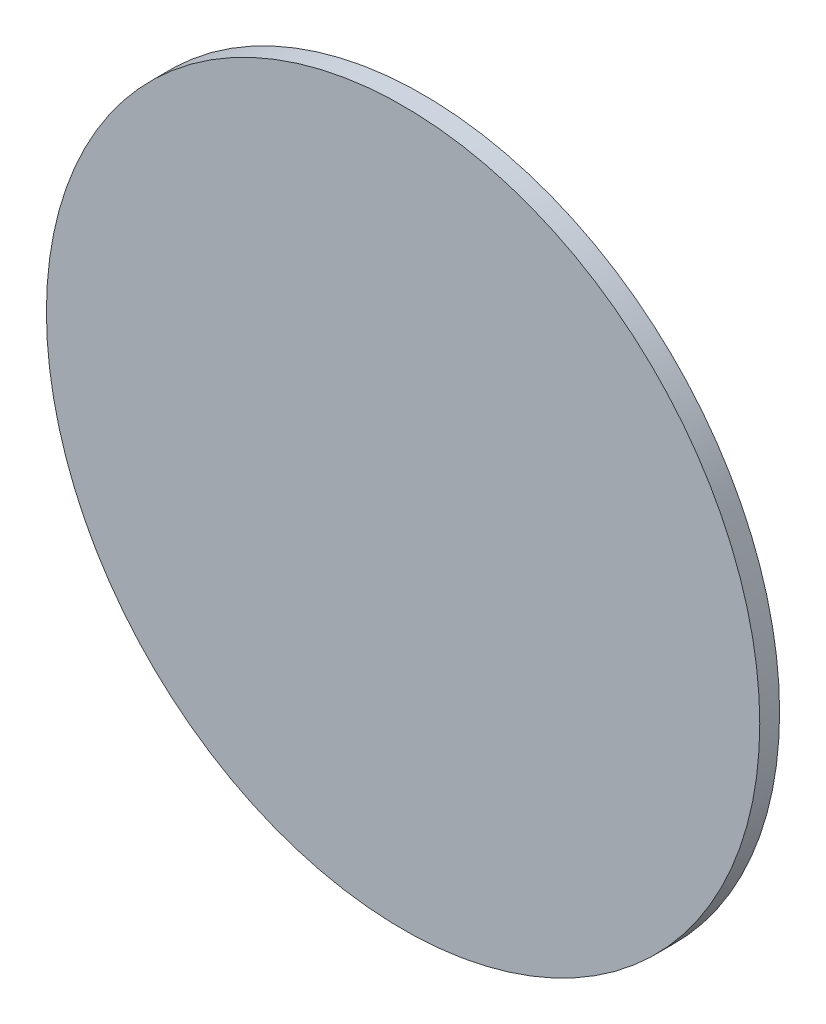
SolidWorks part; units mm, degrees
ref_plane "Front Plane" through (0, 0, 0) normal (0, 0, 1) x (1, 0, 0)
ref_plane "Top Plane" through (0, 0, 0) normal (0, 1, 0) x (1, 0, 0)
ref_plane "Right Plane" through (0, 0, 0) normal (1, 0, 0) x (0, 0, -1)
sketch "Sketch1" plane through (0, 0, 0) normal (0, 0, 1) x (1, 0, 0)
  circle A0 centre (0, 0) radius 90
  dimension "D1" = 180
extrude "Boss-Extrude1" add sketch "Sketch1" along normal mid plane 5 contours A0
